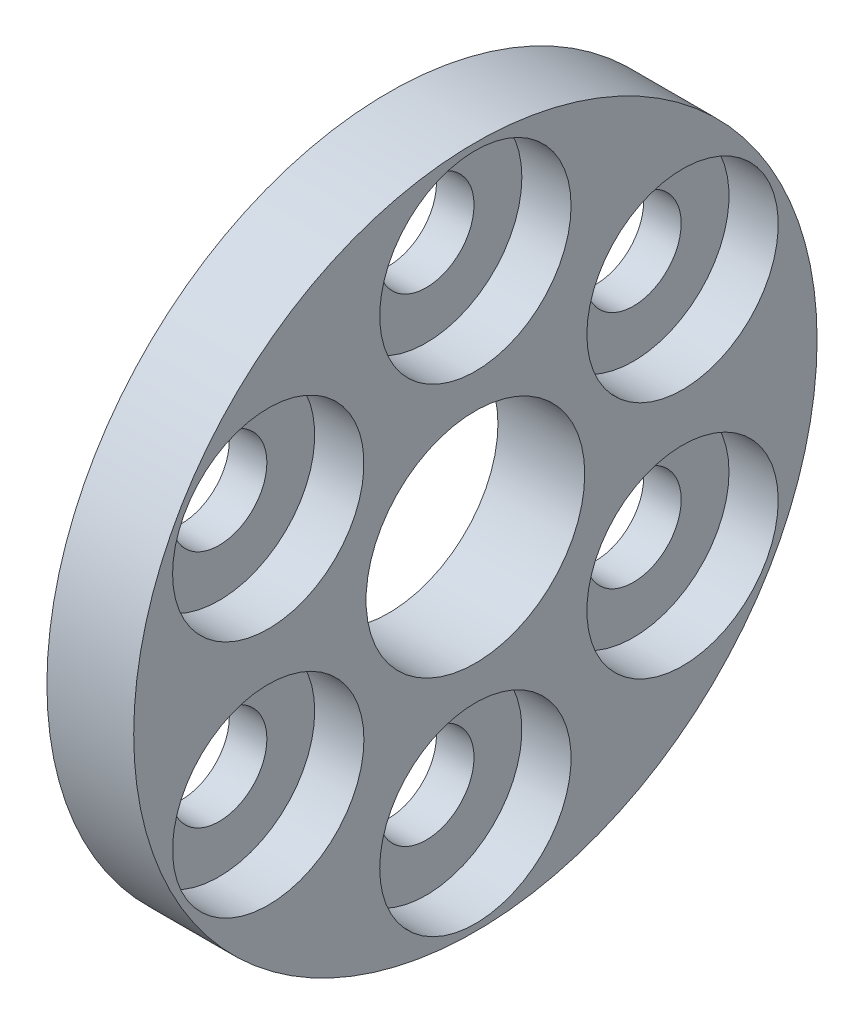
SolidWorks part; units mm, degrees
material "1023 Carbon Steel Sheet (SS)"
ref_plane "Front Plane" through (0, 0, 0) normal (0, 0, 1) x (1, 0, 0)
ref_plane "Top Plane" through (0, 0, 0) normal (0, 1, 0) x (1, 0, 0)
ref_plane "Right Plane" through (0, 0, 0) normal (1, 0, 0) x (0, 0, -1)
sketch "Sketch1" plane through (0, 0, 0) normal (1, 0, 0) x (0, 0, -1)
  circle A0 centre (0, 0) radius 12.5
  dimension "D1" = 25
extrude "Boss-Extrude1" add sketch "Sketch1" along normal blind 3.175
sketch "Sketch2" plane through (3.175, 0, 0) normal (1, 0, 0) x (0, 0, -1)
  circle A0 centre (0, 8.75) radius 1.75
  dimension "D1" = 3.5
  dimension "D2" = 8.75
sketch "Sketch3" plane through (3.175, 0, 0) normal (1, 0, 0) x (0, 0, -1)
  circle A0 centre (0, 0) radius 4
  dimension "D1" = 8
extrude "Cut-Extrude1" cut sketch "Sketch3" against normal through all
extrude "Cut-Extrude2" cut sketch "Sketch2" against normal through all
sketch "Sketch4" plane through (3.175, 0, 0) normal (1, 0, 0) x (0, 0, -1)
  line L1 (1.5877, 11.5) -> (-1.5877, 11.5)
  line L2 (-1.5877, 11.5) -> (-3.1754, 8.75)
  line L3 (-3.1754, 8.75) -> (-1.5877, 6)
  line L4 (-1.5877, 6) -> (1.5877, 6)
  line L5 (1.5877, 6) -> (3.1754, 8.75)
  line L6 (3.1754, 8.75) -> (1.5877, 11.5)
  circle A0 centre (0, 8.75) radius 2.75 construction
  circle A1 centre (0, 8.75) radius 3.5
  circle M13 centre (0, 8.75) radius 1.75
  dimension "D2" = 7
  dimension "D1" = 5.5
extrude "Cut-Extrude3" cut sketch "Sketch4" against normal blind 1.8 contours L5 L6 L1 L2 L3 L4 M13 | A1 L6 L5 L4 L3 L2 L1 | M13
pattern_circular "CirPattern1" count 6 over 360 about axis through (0, 0, 0) along (1, 0, 0) of "Cut-Extrude3", "Cut-Extrude2"
